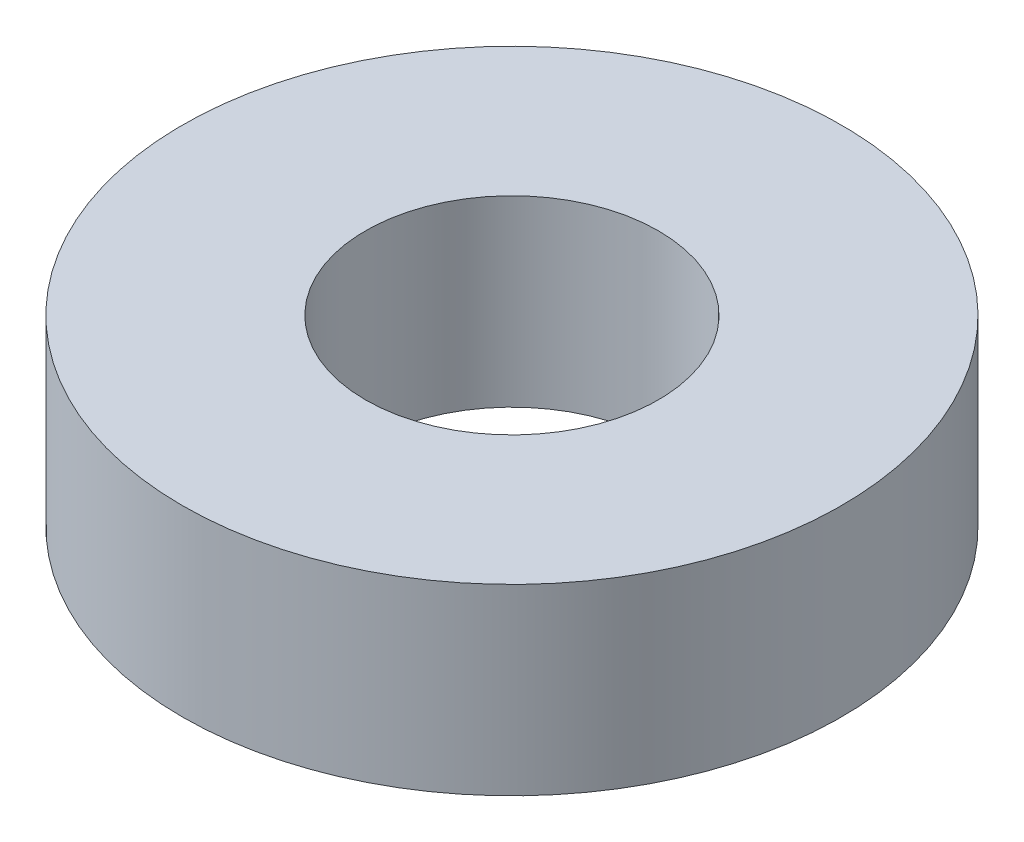
SolidWorks part; units mm, degrees
ref_plane "前视基准面" through (0, 0, 0) normal (0, 0, 1) x (1, 0, 0)
ref_plane "上视基准面" through (0, 0, 0) normal (0, 1, 0) x (1, 0, 0)
ref_plane "右视基准面" through (0, 0, 0) normal (1, 0, 0) x (0, 0, -1)
sketch "草图1" plane through (0, 0, 0) normal (0, 1, 0) x (1, 0, 0)
  circle A0 centre (0, 0) radius 4
  circle A1 centre (0, 0) radius 9
  dimension "D1" = 18
  dimension "D2" = 8
extrude "拉伸1" add sketch "草图1" along normal blind 5
